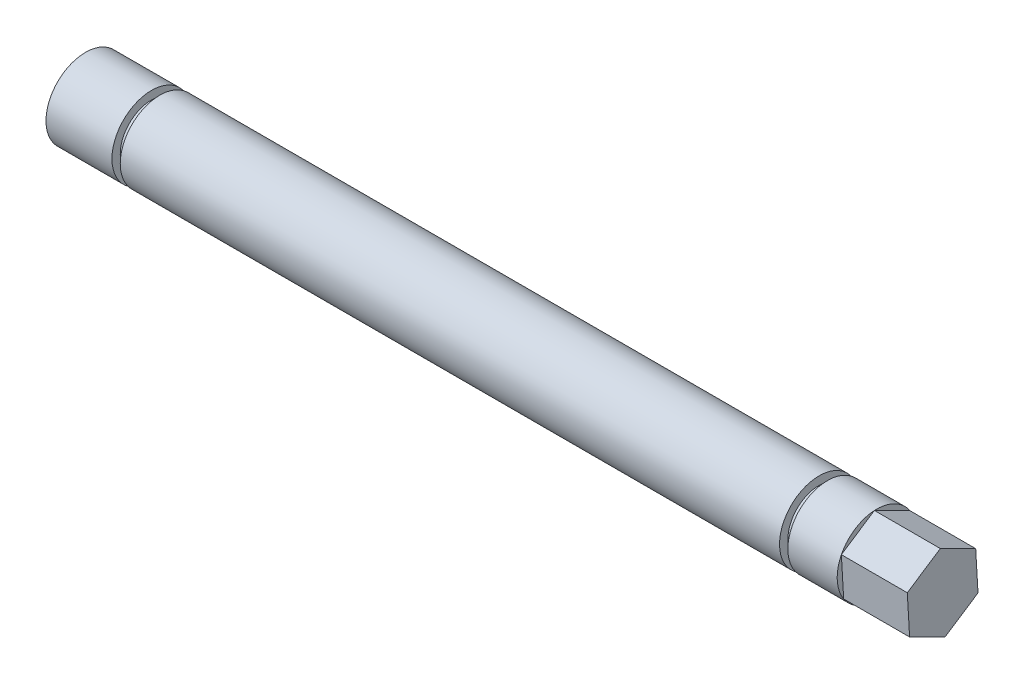
SolidWorks part; units mm, degrees
material "Chrome Stainless Steel"
ref_plane "Front Plane" through (0, 0, 0) normal (0, 0, 1) x (1, 0, 0)
ref_plane "Top Plane" through (0, 0, 0) normal (0, 1, 0) x (1, 0, 0)
ref_plane "Right Plane" through (0, 0, 0) normal (1, 0, 0) x (0, 0, -1)
sketch "Sketch2" plane through (0, 0, 0) normal (1, 0, 0) x (0, 0, -1)
  circle A0 centre (0, 0) radius 7.62
  dimension "D1" = 15.24
extrude "Boss-Extrude1" add sketch "Sketch2" along normal blind 165.1
sketch "Sketch3" plane through (0, 0, 0) normal (0, 0, 1) x (1, 0, 0)
  line L0 (0, 0) -> (94.6086, 0) construction
  line L1 (1316.2087, 0) -> (-1316.2087, 0) construction
  line L2 (165.1, 7.62) -> (0, 7.62) construction
  line L3 (12.7, 7.62) -> (14.3002, 7.62)
  line L4 (12.7, 7.62) -> (12.7, 6.0198)
  line L5 (12.7, 6.0198) -> (14.3002, 6.0198)
  line L6 (14.3002, 7.62) -> (14.3002, 6.0198)
  dimension "D1" = 94.6086
  dimension "D2" = 12.7
  dimension "D3" = 1.6002
revolve "Cut-Revolve1" cut sketch "Sketch3" angle 360 about L0
ref_plane "Plane1" through (141.3002, 0, 0) normal (-1, 0, 0) x (0, 0, 1)
sketch "Sketch4" plane through (141.3002, 0, 0) normal (-1, 0, 0) x (0, 0, 1)
  circle A0 centre (0, 0) radius 7.62 construction
  circle A1 centre (0, 0) radius 6.0198 construction
  circle A2 centre (0, 0) radius 7.62
  circle A3 centre (0, 0) radius 6.0198
extrude "Cut-Extrude1" cut sketch "Sketch4" against normal blind 1.6002 contours A2 | A3
sketch "Sketch5" plane through (165.1, 0, 0) normal (1, 0, 0) x (0, 0, -1)
  line L1 (6.3662, 4.1876) -> (-0.4435, 7.6071)
  line L2 (-0.4435, 7.6071) -> (-6.8097, 3.4195)
  line L3 (-6.8097, 3.4195) -> (-6.3662, -4.1876)
  line L4 (-6.3662, -4.1876) -> (0.4435, -7.6071)
  line L5 (0.4435, -7.6071) -> (6.8097, -3.4195)
  line L6 (6.8097, -3.4195) -> (6.3662, 4.1876)
  circle A0 centre (0, 0) radius 7.62 construction
  circle A1 centre (0, 0) radius 7.62 construction
  dimension "D1" = 6.8097
  dimension "D2" = 3.4195
extrude "Cut-Extrude2" cut sketch "Sketch5" against normal blind 12.7 flip side to cut
